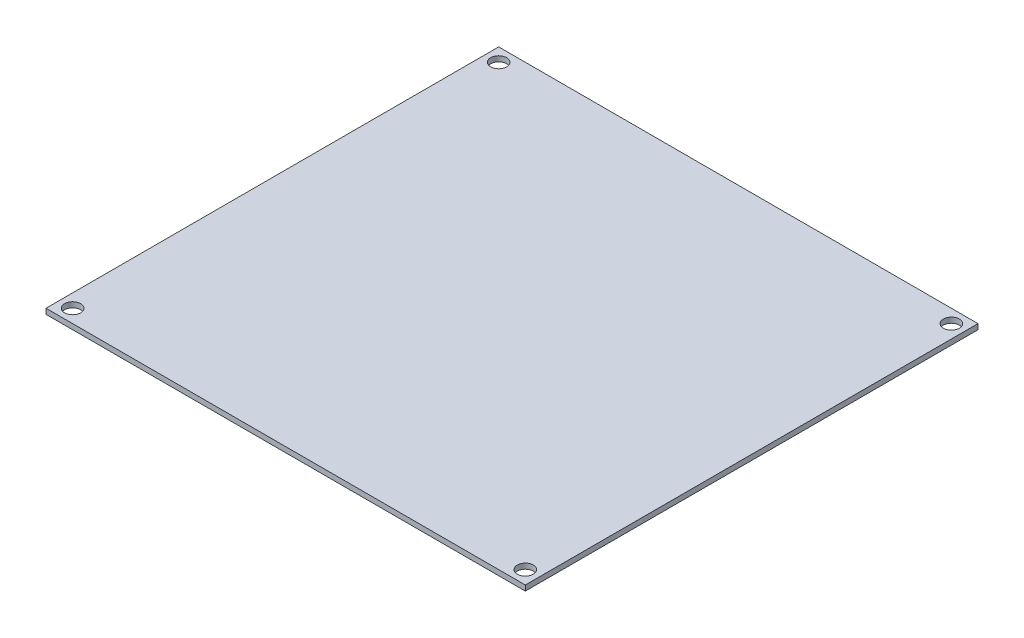
SolidWorks part; units mm, degrees
ref_plane "Спереди" through (0, 0, 0) normal (0, 0, 1) x (1, 0, 0)
ref_plane "Сверху" through (0, 0, 0) normal (0, 1, 0) x (1, 0, 0)
ref_plane "Справа" through (0, 0, 0) normal (1, 0, 0) x (0, 0, -1)
sketch "Sketch1" plane through (0, 0, 0) normal (0, 1, 0) x (1, 0, 0)
  line L3 (-90, 85) -> (90, 85)
  line L5 (-90, 85) -> (-90, -85)
  line L6 (-90, -85) -> (90, -85)
  line L7 (90, 85) -> (90, -85)
  circle A0 centre (-85, -80) radius 3
  circle A1 centre (85, -80) radius 3
  circle A2 centre (-85, 80) radius 3
  circle A3 centre (85, 80) radius 3
extrude "Boss-Extrude1" add sketch "Sketch1" along normal blind 2
